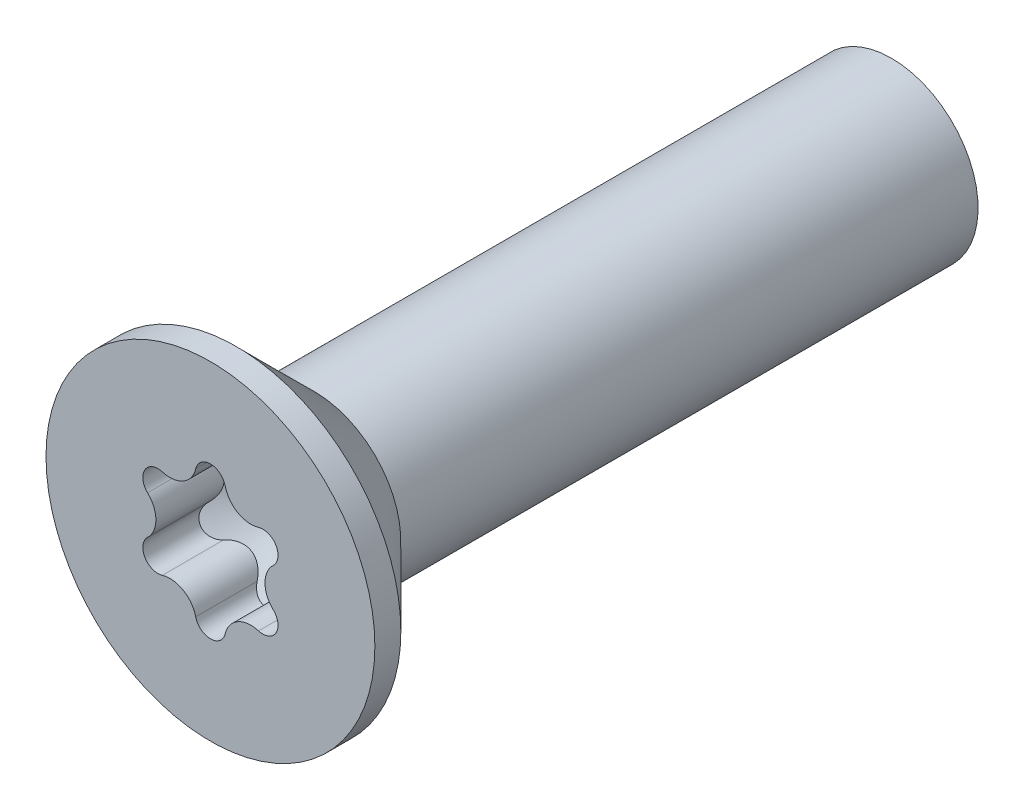
SolidWorks part; units mm, degrees
material "Plain Carbon Steel"
ref_plane "Front Plane" through (0, 0, 0) normal (0, 0, 1) x (1, 0, 0)
ref_plane "Top Plane" through (0, 0, 0) normal (0, 1, 0) x (1, 0, 0)
ref_plane "Right Plane" through (0, 0, 0) normal (1, 0, 0) x (0, 0, -1)
sketch "BodySke" plane through (0, 0, 0) normal (1, 0, 0) x (0, 0, -1)
  line L0 (0, 0) -> (-1787.2758, 0) construction
  line L1 (0, 0) -> (0, 1.9)
  line L2 (0.3, 1.9) -> (1.2, 1)
  line L3 (0.3, -1.9) -> (1.2, -1) construction
  line L4 (1.2, 1) -> (8, 1)
  line L5 (8, 1) -> (8, 0)
  line L6 (8, 0) -> (0, 0)
  line L7 (0, 0) -> (0, 50000) construction
  line L8 (0.3, 1.9) -> (0, 1.9)
  dimension "D" = 2
  dimension "Dk" = 3.8
  dimension "K" = 1.2
  dimension "L" = 8
  dimension "D1" = 90
  dimension "B" = 8
revolve "Base-Revolve" add sketch "BodySke" angle 360 about L0
cosmetic thread "ThreadCosmetic" [suppressed] parameters "ThdLen"=6.8, "MinorDia"=1.548
sketch "PreBSke" plane through (0, 0, 0) normal (1, 0, 0) x (0, 0, -1)
  line L0 (0, 0) -> (-50000, 0) construction
  line L1 (0, 0) -> (0, 0.875)
  line L2 (0, 2.2) -> (0, -2.2) construction
  line L3 (0, 0.875) -> (0.64, 0.875)
  line L4 (0.64, 0.875) -> (1.1658, 0)
  line L5 (1.1658, 0) -> (0, 0)
  line L6 (0.64, -0.875) -> (1.1658, 0) construction
  dimension "T" = 0.64
  dimension "A" = 1.75
  dimension "D1" = 118
revolve "PreBroach" cut sketch "PreBSke" angle 360 about L0
sketch "HexSke" plane through (0, 0, 0) normal (0, 0, 1) x (1, 0, 0)
  line L0 (0, 0) -> (-43301.2702, 25000) construction
  line L1 (0, 0) -> (-43301.2702, -25000) construction
  line L2 (0, 0) -> (50000, 0) construction
  arc A0 (-0.7263, -0.2227) -> (-0.7263, 0.2227) centre (-0.9365, 0) ccw
  arc A1 (-0.7578, 0.4375) -> (-0.7263, 0.2227) centre (-0.6062, 0.35) ccw
  arc A2 (-0.7263, -0.2227) -> (-0.7578, -0.4375) centre (-0.6062, -0.35) ccw
  arc A3 (-0.5561, 0.5177) -> (-0.7578, 0.4375) centre (-0.6062, 0.35) ccw
  circle A4 centre (0, 0) radius 0.6303 construction
  circle A5 centre (0, 0) radius 0.875 construction
  arc A6 (-0.5561, 0.5177) -> (-0.1703, 0.7404) centre (-0.4683, 0.8111) ccw
  arc A7 (0, 0.875) -> (-0.1703, 0.7404) centre (0, 0.7) ccw
  arc A8 (0.1703, 0.7404) -> (0, 0.875) centre (0, 0.7) ccw
  arc A9 (0.1703, 0.7404) -> (0.5561, 0.5177) centre (0.4683, 0.8111) ccw
  arc A10 (0.7578, 0.4375) -> (0.5561, 0.5177) centre (0.6062, 0.35) ccw
  arc A11 (0.7263, 0.2227) -> (0.7578, 0.4375) centre (0.6062, 0.35) ccw
  arc A12 (0.7263, 0.2227) -> (0.7263, -0.2227) centre (0.9365, 0) ccw
  arc A13 (0.7578, -0.4375) -> (0.7263, -0.2227) centre (0.6062, -0.35) ccw
  arc A14 (0.5561, -0.5177) -> (0.7578, -0.4375) centre (0.6062, -0.35) ccw
  arc A15 (0.5561, -0.5177) -> (0.1703, -0.7404) centre (0.4683, -0.8111) ccw
  arc A16 (0, -0.875) -> (0.1703, -0.7404) centre (0, -0.7) ccw
  arc A17 (-0.1703, -0.7404) -> (0, -0.875) centre (0, -0.7) ccw
  arc A18 (-0.1703, -0.7404) -> (-0.5561, -0.5177) centre (-0.4683, -0.8111) ccw
  arc A19 (-0.7578, -0.4375) -> (-0.5561, -0.5177) centre (-0.6062, -0.35) ccw
  circle A20 centre (0, 0) radius 0.875 construction
  circle A21 centre (0, 0) radius 0.875
  point P56 (0, 0)
  circle M6 centre (0, 0) radius 0.875
  dimension "B" = 1.2605
  dimension "Ri" = 0.175
  dimension "Re" = 0.3062
  dimension "D1" = 60
  dimension "D5" = 6
extrude "Hexalobular" add sketch "HexSke" against normal up to next contours A2 A0 A1 M6 | A7 A3 A6 M6 | A10 A8 A9 M6 | A13 A11 A12 M6 | A16 A14 A15 M6 | A19 A17 A18 M6
sketch "ThdSchSke" plane through (0, 0, 0) normal (1, 0, 0) x (0, 0, -1)
  line L0 (8.1305, 1) -> (8, 0.774)
  line L1 (8, 0.774) -> (7.8695, 1)
  line L2 (7.8695, 1) -> (8.1305, 1)
  line L3 (8, 0.774) -> (8, 1) construction
  line L4 (8, -1) -> (8, 1) construction
  line L5 (8, 1) -> (1.2, 1) construction
  line L6 (0, 0) -> (-50000, 0) construction
  dimension "MinorDia" = 1.548
  dimension "D1" = 60
  dimension "D2" = 0.261
revolve "ThreadSchematic" cut sketch "ThdSchSke" angle 360 about L6
ref_plane "ThreadPlane" through (0, 0, -1.2) normal (0, 0, -1) x (-1, 0, 0)
pattern_linear "ThdSchPat" [suppressed] count 11
equation "\"MinorDia@ThreadCosmetic\" = \"MinorDia@ThdSchSke\""
equation "\"ThdLen@ThreadCosmetic\" = \"ThreadLength\""
equation "\"Ri@HexSke\"= .1 * \"A@PreBSke\""
equation "\"Re@HexSke\"= .175 * \"A@PreBSke\""
equation "\"ThreadLength\"= IIF ( \"B@BodySke\" = \"L@BodySke\" , \"L@BodySke\" - \"K@BodySke\" , \"B@BodySke\" )"
equation "\"ThdLen@ThreadPlane\"=\"ThreadLength\""
